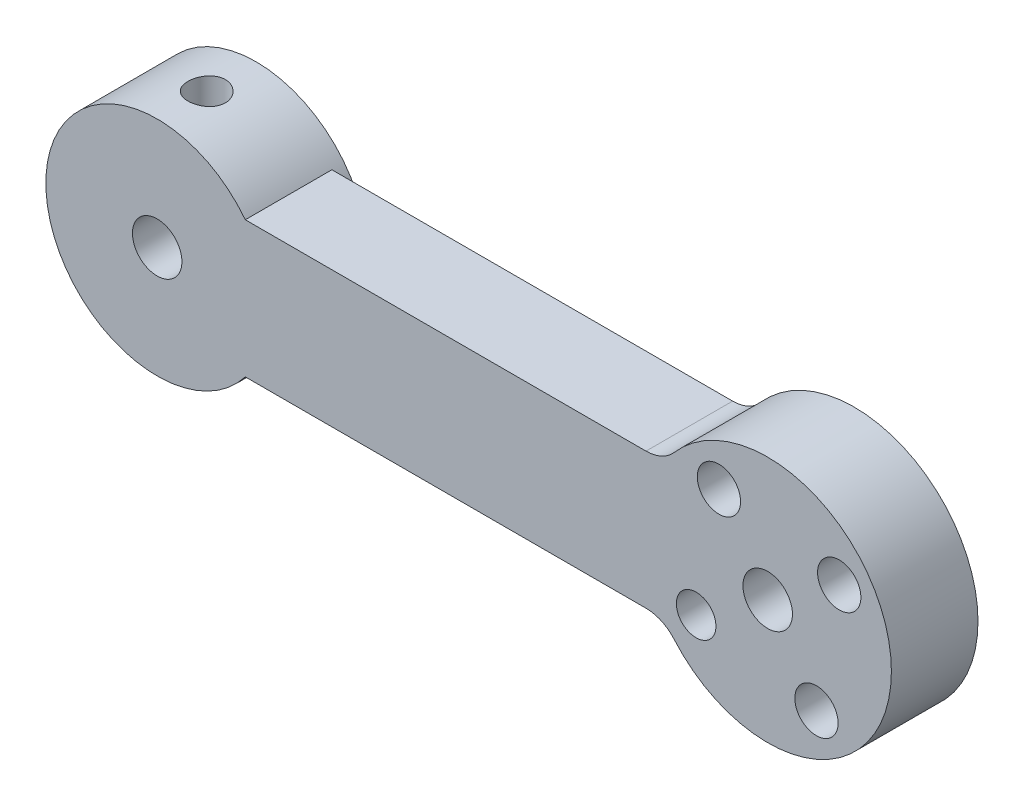
SolidWorks part; units mm, degrees
ref_plane "Front Plane" through (0, 0, 0) normal (0, 0, 1) x (1, 0, 0)
ref_plane "Top Plane" through (0, 0, 0) normal (0, 1, 0) x (1, 0, 0)
ref_plane "Right Plane" through (0, 0, 0) normal (1, 0, 0) x (0, 0, -1)
sketch "Sketch1" plane through (0, 0, 0) normal (0, 0, 1) x (1, 0, 0)
  line L0 (0, 11) -> (0, 0)
  line L1 (0, 0) -> (45, 0)
  line L3 (0, 11) -> (45, 11)
  arc A0 (45, 11) -> (45, 0) centre (53.3516, 5.5) cw
  dimension "D3" = 10
  dimension "D1" = 11
  dimension "D2" = 45
  dimension "D4" = 11
extrude "Boss-Extrude1" add sketch "Sketch1" along normal blind 7
sketch "Sketch2" plane through (0, 0, 7) normal (0, 0, 1) x (1, 0, 0)
  line L0 (22.5, 11) -> (22.5, 0) construction
  line L1 (45, 11) -> (0, 11) construction
  line L2 (0, 0) -> (45, 0) construction
  circle A0 centre (53.3516, 5.5) radius 2
  circle A1 centre (-8.3516, 5.5) radius 2
  dimension "D1" = 4
extrude "Cut-Extrude1" cut sketch "Sketch2" against normal through all
fillet "Fillet11" radius 3 2 edges at (45, 11, 3.5) (45, 0, 3.5)
sketch "Sketch31" plane through (0, 0, 7) normal (0, 0, 1) x (1, 0, 0)
  point P14 (77.9816, -9.7921)
sketch "Sketch32" plane through (0, 0, 7) normal (0, 0, 1) x (1, 0, 0)
  line L0 (43.5155, 11) -> (0, 11) construction
  line L2 (0, 11) -> (0, 0) construction
  circle A0 centre (4, 5.5) radius 2
  dimension "D1" = 4
  dimension "D2" = 5.5
  dimension "D3" = 4
extrude "Cut-Extrude14" cut sketch "Sketch32" against normal through all
sketch "Sketch33" plane through (0, 0, 7) normal (0, 0, 1) x (1, 0, 0)
  circle A0 centre (4, 5.5) radius 9
  circle A1 centre (4, 5.5) radius 2
  dimension "D1" = 4
  dimension "D2" = 18
extrude "Boss-Extrude2" add sketch "Sketch33" against normal blind 8
sketch "Sketch35" plane through (0, 0, 0) normal (0, 0, -1) x (-1, 0, 0)
  circle A0 centre (-53.3516, 5.5) radius 7 construction
  circle A1 centre (-47.5677, 1.5571) radius 1.6
  circle A2 centre (-57.2945, -0.2839) radius 1.75
  circle A3 centre (-59.1356, 9.4429) radius 1.75
  circle A4 centre (-49.4088, 11.2839) radius 1.75
  dimension "D1" = 14
  dimension "D2" = 3.2
  dimension "D3" = 3.5
  dimension "D4" = 3.5
  dimension "D5" = 3.5
sketch "Sketch36" plane through (0, 0, 0) normal (0, 0, -1) x (-1, 0, 0)
extrude "Cut-Extrude15" cut sketch "Sketch35" against normal through all
ref_plane "Plane1" through (0, 5.5, 0) normal (0, 1, 0) x (1, 0, 0)
sketch "Sketch37" plane through (0, 5.5, 0) normal (0, 1, 0) x (1, 0, 0)
  line L0 (13, 1) -> (-5, 1) construction
  line L1 (-5, 1) -> (-5, -7) construction
  circle A0 centre (4, -3) radius 1.51
  dimension "D3" = 3.02
  dimension "D1" = 4
  dimension "D2" = 9
extrude "Cut-Extrude16" cut sketch "Sketch37" against normal through all and the other way through all
